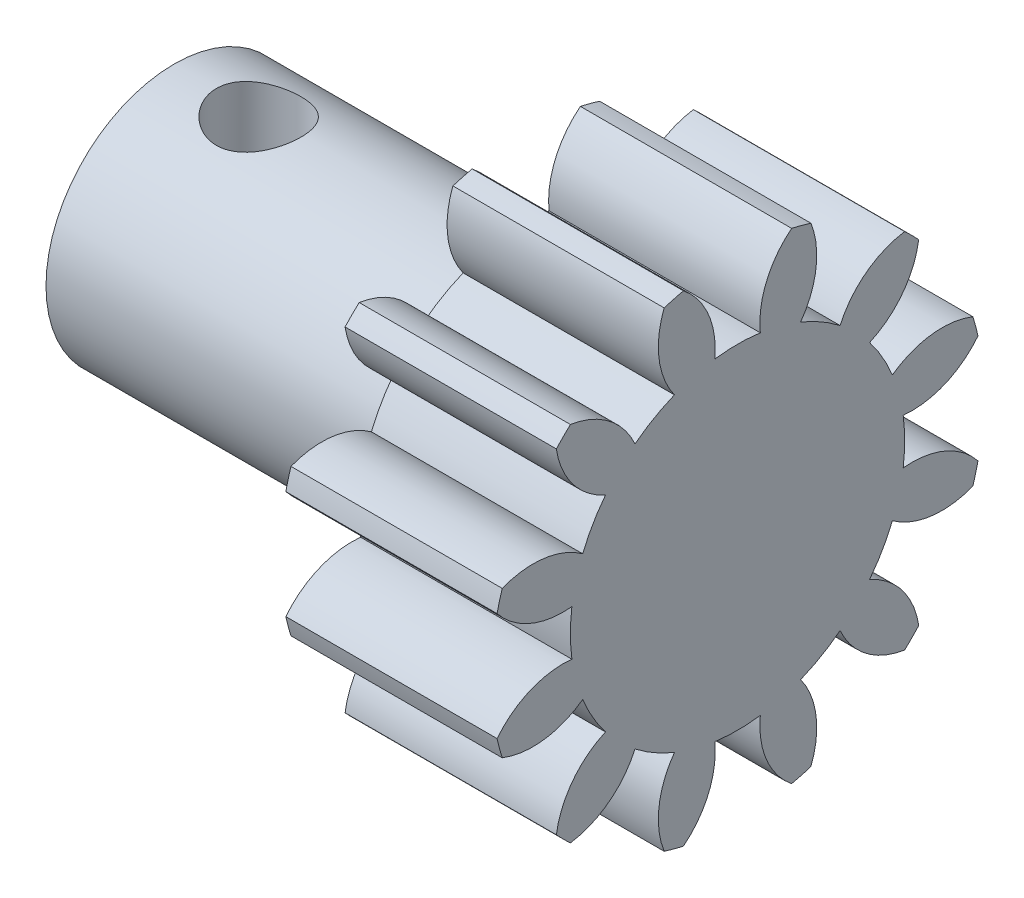
SolidWorks part; units mm, degrees
ref_plane "Plane1" through (0, 0, 0) normal (0, 0, 1) x (1, 0, 0)
ref_plane "Plane2" through (0, 0, 0) normal (0, 1, 0) x (1, 0, 0)
ref_plane "Plane3" through (0, 0, 0) normal (1, 0, 0) x (0, 0, -1)
sketch "HoldingSke" plane through (0, 0, 0) normal (0, 1, 0) x (1, 0, 0)
  line L0 (0, 0) -> (397.5192, -84.4953)
  line L1 (-15, 0) -> (100, 0) construction
  line L2 (0, 0) -> (-2.1039, 2.3779)
  line L3 (0, 0) -> (-11.863, 4.5341)
  line L4 (0, 0) -> (8.4473, 1.7955)
  line L5 (0, 0) -> (-47.5972, -17.7524)
  line L6 (0, 0) -> (-7.8959, -5.3274)
  line L7 (-2.1039, 2.3779) -> (8.8308, 51.9871)
  line L8 (-76.2, 54.61) -> (-69.596, 54.61)
  line L9 (-67.7845, 28.3722) -> (-49.3413, 33.142)
  line L10 (-76.2, 71.12) -> (104.1128, 71.12)
  line L11 (0, 0) -> (-9.525, 0)
  line L12 (-76.2, 101.6) -> (-76.1428, 101.6)
  line L13 (24.9733, 27.94) -> (52.9518, 28.4284)
  line L14 (24.9733, 27.94) -> (24.9746, 27.94)
  line L15 (24.9733, 27.94) -> (100.4006, 29.5858)
  circle A0 centre (0, 0) radius 3.175
  circle A1 centre (0, 0) radius 7.5394
  circle A2 centre (0, 0) radius 38.1
  circle A3 centre (0, 0) radius 3.175
  dimension "MHD" = 15.0787
  dimension "Hub_dia" = 76.2
  dimension "Bore" = 6.35
  dimension "MBD" = 6.35
  dimension "Num_teeth" = 12
  dimension "Pitch" = 406.4
  dimension "Overall_len" = 50.8
  dimension "Show_teeth" = 12
  dimension "Thickness" = 9.525
  dimension "OAL" = 50.8001
  dimension "T_dim" = 6.604
  dimension "Ap" = 14.5
  dimension "H" = 19.05
  dimension "Pitch_radius" = 180.3128
  dimension "Width" = 9.525
  dimension "Backlash" = 0.0571
  dimension "Addendum_fac" = 1
  dimension "Dedendum_fac" = 1.25
  dimension "Clearance_fac" = 0.25
  dimension "Dedendum_add" = 0.0013
sketch "BasProSke" plane through (0, 0, 0) normal (0, 1, 0) x (1, 0, 0)
  line L0 (-10, 0) -> (60, 0) construction
  line L1 (0, 0) -> (0, 11.1125)
  line L2 (0, 0) -> (9.525, 0)
  line L3 (9.525, 0) -> (9.525, 11.1125)
  line L4 (9.525, 11.1125) -> (0, 11.1125)
  dimension "Thickness" = 9.525
  dimension "Diameter" = 22.225
revolve "Base-Revolve" add sketch "BasProSke" angle 360 about L0
sketch "TooCutSke" plane through (0, 0, 0) normal (1, 0, 0) x (0, 0, -1)
  line L1 (0, 0) -> (0, 107) construction
  line L2 (0, 0) -> (-1.3431, 9.4298) construction
  line L3 (0, 0) -> (-4.8949, 18.2679) construction
  line L4 (-1.3431, 9.4298) -> (-2.4474, 9.1339) construction
  arc A0 (1.0269, 7.4691) -> (-1.0269, 7.4691) centre (0, 0) ccw
  arc A1 (2.4651, 10.8617) -> (-2.4651, 10.8617) centre (0, 0) ccw
  circle A2 centre (0, 0) radius 9.525 construction
  circle A3 centre (0, 0) radius 9.2216 construction
  arc A4 (-1.0269, 7.4691) -> (-2.4651, 10.8617) centre (-4.8164, 7.8638) ccw
  arc A5 (2.4651, 10.8617) -> (1.0269, 7.4691) centre (4.8164, 7.8638) ccw
  dimension "Root_dia" = 15.0787
  dimension "Overcut_dia" = 22.2758
  dimension "Pitch_dia" = 19.05
  dimension "Base_dia" = 18.4432
  dimension "Flank_rad" = 3.81
  dimension "Half_ang" = 15
  dimension "Half_CT" = 1.1432
extrude "ToothCut" cut sketch "TooCutSke" along normal through all
fillet "Breaks" [suppressed] radius 0.0318
fillet "RootFillets" [suppressed] radius 0.3981
pattern_circular "TeethCuts" count 12 over 360 about axis through (0, 0, 0) along (1, 0, 0) of "ToothCut", "RootFillets", "Breaks"
sketch "HubNeaOneSke" plane through (0, 0, 0) normal (-1, 0, 0) x (0, 0, 1)
  circle A0 centre (0, 0) radius 7.5394
  dimension "Diameter" = 15.0787
extrude "HubNearOne" [suppressed] add sketch "HubNeaOneSke" along normal blind 41.2751
sketch "HubNeaBotSke" plane through (0, 0, 0) normal (-1, 0, 0) x (0, 0, 1)
  circle A0 centre (0, 0) radius 7.5394
  dimension "Diameter" = 15.0787
extrude "HubNearBoth" [suppressed] add sketch "HubNeaBotSke" along normal blind 20.6375
ref_plane "FarPln" through (9.525, 0, 0) normal (1, 0, 0) x (0, 0, -1)
sketch "HubFarSke" plane through (9.525, 0, 0) normal (1, 0, 0) x (0, 0, -1)
  circle A0 centre (0, 0) radius 7.5394
  dimension "Diameter" = 15.0787
extrude "HubFar" [suppressed] add sketch "HubFarSke" along normal blind 20.6375
sketch "BorSke" plane through (0, 0, 0) normal (1, 0, 0) x (0, 0, -1)
  circle A0 centre (0, 0) radius 3.175
  dimension "Diameter" = 6.35
extrude "Bore" cut sketch "BorSke" along normal mid plane 101.6001
sketch "KeySke" plane through (0, 0, 0) normal (1, 0, 0) x (0, 0, -1)
  line L0 (-0.127, 0) -> (-0.127, 3.429)
  line L1 (-0.127, 3.429) -> (0.127, 3.429)
  line L2 (0.127, 3.429) -> (0.127, 0)
  line L3 (0, 0) -> (0, 34) construction
  line L4 (-0.127, 0) -> (0.127, 0)
  dimension "Offset" = 3.429
  dimension "Width" = 0.254
extrude "Keyway" [suppressed] cut sketch "KeySke" along normal mid plane 101.6001
pattern_circular "Keyway2" [suppressed] count 2 every 90 about axis through (-10, 0, 0) along (1, 0, 0)
sketch "Sketch1" plane through (0, 0, 0) normal (1, 0, 0) x (0, 0, -1)
  circle A0 centre (0, 0) radius 9.525 construction
  dimension "D1" = 19.05
sketch "Sketch2" plane through (9.525, 0, 0) normal (1, 0, 0) x (0, 0, -1)
  circle A0 centre (0, 0) radius 7.5394
  arc A2 (-5.955, 4.6239) -> (-6.9819, 2.8452) centre (0, 0) ccw construction
extrude "Boss-Extrude1" add sketch "Sketch2" against normal blind 25.4
sketch "Sketch3" plane through (-15.875, 0, 0) normal (-1, 0, 0) x (0, 0, 1)
  line L0 (-1.778, 2.8575) -> (1.778, 2.8575)
  line L1 (0, 2.8575) -> (0, -3.3655) construction
  arc A0 (-1.778, 2.8575) -> (1.778, 2.8575) centre (0, 0) ccw
  dimension "D1" = 6.731
  dimension "D2" = 6.223
extrude "Cut-Extrude1" cut sketch "Sketch3" against normal blind 20
sketch "Sketch5" plane through (0, 2.8575, 0) normal (0, -1, 0) x (1, 0, 0)
  line L0 (-15.875, 7.5394) -> (-15.875, -7.5394) construction
  line L1 (0, -9.525) -> (0, 9.525) construction
  line L2 (-15.875, 0) -> (0, 0) construction
  circle A0 centre (-12.065, 0) radius 1.905
  dimension "D1" = 3.81
  dimension "D2" = 3.81
extrude "Cut-Extrude2" cut sketch "Sketch5" against normal through all
sketch "Sketch6" plane through (-15.875, 0, 0) normal (-1, 0, 0) x (0, 0, 1)
  circle A0 centre (0, 0) radius 5.7785
  circle A1 centre (0, 0) radius 12.7
  dimension "D1" = 11.557
  dimension "D2" = 25.4
extrude "Cut-Extrude3" cut sketch "Sketch6" against normal up to surface (15.875 mm away) up to face at (0, 2.4175, -9.0221)
equation "' \"Pitch@HoldingSke\" = 4"
equation "' \"Num_teeth@HoldingSke\" = 12"
equation "' \"Ap@HoldingSke\" =  20"
equation "' \"Ap@HoldingSke\" = 20"
equation "' \"Width@HoldingSke\" = 0.5"
equation "' \"Hub_dia@HoldingSke\"= 1"
equation "' \"Hub_dia@HoldingSke\" = 1"
equation "' \"Overall_len@HoldingSke\" = 1.0"
equation "' \"Bore@HoldingSke\" = 0.75"
equation "' \"T_dim@HoldingSke\" = 0.85"
equation "' \"Width@KeySke\" = 0.25"
equation "' \"Show_teeth@HoldingSke\" = 13"
equation "' \"Backlash@HoldingSke\" = 0.009"
equation "' \"Addendum_fac@HoldingSke\" = 1.0"
equation "' \"Dedendum_fac@HoldingSke\" = 1.25"
equation "' \"Dedendum_add@HoldingSke\" = 0.00005"
equation "' \"Clearance_fac@HoldingSke\" = 0.25"
equation "' \"Pitch@HoldingSke\" = 0.5"
equation "' \"Num_teeth@HoldingSke\" = 23"
equation "' \"Show_teeth@HoldingSke\" = 23"
equation "' \"Backlash@HoldingSke\" = 0.0375"
equation "\"Overcut_dia@TooCutSke\" = (\"Num_teeth@HoldingSke\" + 2 * \"Addendum_fac@HoldingSke\") / \"Pitch@HoldingSke\" + 0.002"
equation "\"Pitch_dia@TooCutSke\" = \"Num_teeth@HoldingSke\" / \"Pitch@HoldingSke\""
equation "\"Base_dia@TooCutSke\" = \"Num_teeth@HoldingSke\" / \"Pitch@HoldingSke\" * cos((\"Ap@HoldingSke\"  * 3.14159265 / 180))"
equation "\"Root_dia@TooCutSke\" = (\"Num_teeth@HoldingSke\" + 2) / \"Pitch@HoldingSke\" - 2 * (\"Addendum_fac@HoldingSke\" + \"Dedendum_fac@HoldingSke\") / \"Pitch@HoldingSke\" - \"Dedendum_add@HoldingSke\" * 2"
equation "\"Half_ang@TooCutSke\" = 180 / \"Num_teeth@HoldingSke\""
equation "\"Half_CT@TooCutSke\" = \"Num_teeth@HoldingSke\" / \"Pitch@HoldingSke\" * sin((3.14159265 / 2 / \"Num_teeth@HoldingSke\")) / 2 - 7 * \"Backlash@HoldingSke\" / 4"
equation "\"Flank_rad@TooCutSke\" = \"Num_teeth@HoldingSke\" / \"Pitch@HoldingSke\" / 5"
equation "\"Radius@RootFillets\" = \"Clearance_fac@HoldingSke\" / \"Pitch@HoldingSke\" + \"Dedendum_add@HoldingSke\""
equation "\"Break_rad@Breaks\" = 0.02 / \"Pitch@HoldingSke\""
equation "\"Thickness@HoldingSke\" = \"Width@HoldingSke\""
equation "\"OAL@HoldingSke\" = \"Thickness@HoldingSke\""
equation "\"MHD@HoldingSke\" = (\"Num_teeth@HoldingSke\" + 2) / \"Pitch@HoldingSke\" - 2 * (\"Addendum_fac@HoldingSke\" + \"Dedendum_fac@HoldingSke\")  / \"Pitch@HoldingSke\" - \"Dedendum_add@HoldingSke\" * 2"
equation "\"MBD@HoldingSke\" = (\"Num_teeth@HoldingSke\" + 2) / \"Pitch@HoldingSke\" - 2 * (\"Addendum_fac@HoldingSke\" + \"Dedendum_fac@HoldingSke\")  / \"Pitch@HoldingSke\" - \"Dedendum_add@HoldingSke\" * 2 - 0.002"
equation "\"MHD@HoldingSke\" = ((sgn( \"MHD@HoldingSke\" - \"Hub_dia@HoldingSke\" )-1)*( \"MHD@HoldingSke\" - \"Hub_dia@HoldingSke\" ))/-2+ \"Hub_dia@HoldingSke\""
equation "\"MBD@HoldingSke\" = ((sgn( \"MBD@HoldingSke\" - \"Bore@HoldingSke\" )-1)*( \"MBD@HoldingSke\" - \"Bore@HoldingSke\" ))/-2+ \"Bore@HoldingSke\""
equation "\"OAL@HoldingSke\" = ((sgn( \"OAL@HoldingSke\" - \"Overall_len@HoldingSke\" )+1)*( \"OAL@HoldingSke\" - \"Overall_len@HoldingSke\" ))/2 + \"Overall_len@HoldingSke\" + 0.000002"
equation "\"Num_teeth@TeethCuts\" = int( \"Show_teeth@HoldingSke\" ) + 1"
equation "\"Num_teeth@TeethCuts\" = ((sgn( \"Num_teeth@TeethCuts\" - \"Num_teeth@HoldingSke\" )-1)*( \"Num_teeth@TeethCuts\" - \"Num_teeth@HoldingSke\" ))/-2+ \"Num_teeth@HoldingSke\""
equation "\"Num_teeth@TeethCuts\" = ((sgn( \"Num_teeth@TeethCuts\" - 2.0)+1)*( \"Num_teeth@TeethCuts\" - 2.0))/2 +2.0"
equation "\"Angle@TeethCuts\" = 360.0 / \"Num_teeth@HoldingSke\""
equation "\"Diameter@BasProSke\" = (\"Num_teeth@HoldingSke\" + 2 * \"Addendum_fac@HoldingSke\") / \"Pitch@HoldingSke\""
equation "\"Thickness@BasProSke\"  = \"Thickness@HoldingSke\""
equation "' \"Fillet_rad@BasProSke\" =  \"Thickness@HoldingSke\" * 0.05"
equation "' \"Fillet_rad@BasProSke\" = \"Thickness@HoldingSke\" * 0.05"
equation "\"MHD@HoldingSke\" = ((sgn( \"MHD@HoldingSke\" - \"Root_dia@TooCutSke\" )-1)*( \"MHD@HoldingSke\" - \"Root_dia@TooCutSke\" ))/-2+ \"Root_dia@TooCutSke\""
equation "\"Diameter@HubNeaOneSke\" = \"MHD@HoldingSke\""
equation "\"Length@HubNearOne\" = \"OAL@HoldingSke\" - \"Thickness@BasProSke\""
equation "\"Diameter@HubNeaBotSke\" = \"MHD@HoldingSke\""
equation "\"Length@HubNearBoth\" = ( \"OAL@HoldingSke\" - \"Thickness@BasProSke\" ) / 2.0"
equation "\"Thickness@FarPln\" = \"Thickness@BasProSke\""
equation "\"Diameter@HubFarSke\" = \"MHD@HoldingSke\""
equation "\"Length@HubFar\" = ( \"OAL@HoldingSke\" - \"Thickness@BasProSke\" ) / 2.0"
equation "\"Diameter@BorSke\" = \"MBD@HoldingSke\""
equation "\"D1@Bore\" = \"OAL@HoldingSke\" * 2.0"
equation "\"D1@Keyway\" = \"OAL@HoldingSke\" * 2.0"
equation "\"Offset@KeySke\" = \"T_dim@HoldingSke\" - \"MBD@HoldingSke\" / 2.0"
